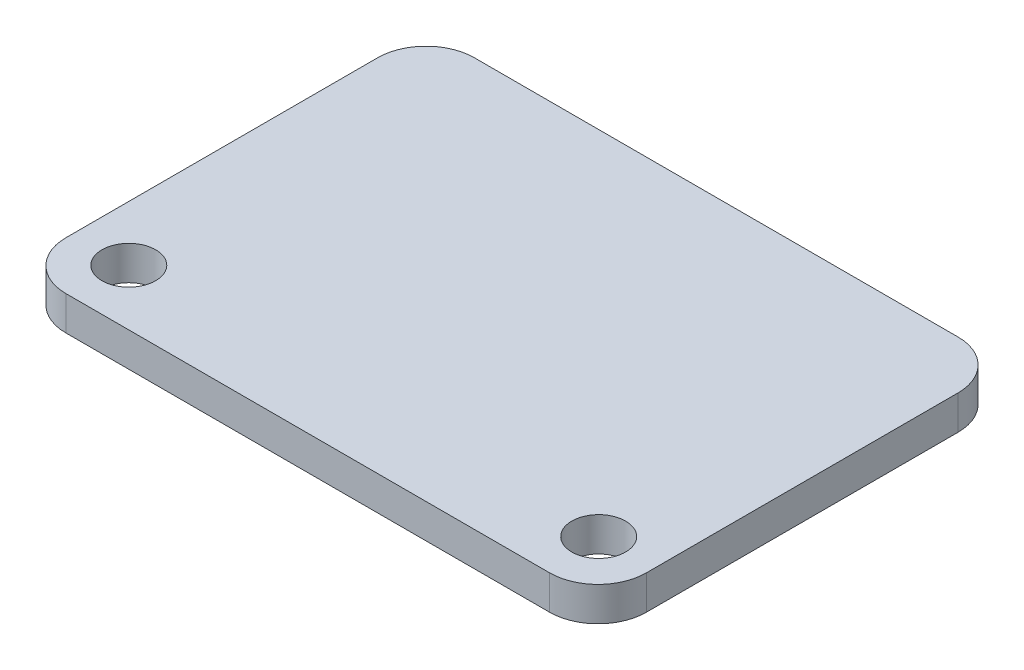
SolidWorks part; units mm, degrees
ref_plane "Front Plane" through (0, 0, 0) normal (0, 0, 1) x (1, 0, 0)
ref_plane "Top Plane" through (0, 0, 0) normal (0, 1, 0) x (1, 0, 0)
ref_plane "Right Plane" through (0, 0, 0) normal (1, 0, 0) x (0, 0, -1)
sketch "Sketch1" plane through (0, 0, 0) normal (0, 1, 0) x (1, 0, 0)
  line L1 (-13.5, -9.5) -> (13.5, -9.5)
  line L2 (-13.5, -9.5) -> (-13.5, 9.5)
  line L3 (-13.5, 9.5) -> (13.5, 9.5)
  line L4 (13.5, -9.5) -> (13.5, 9.5)
  line L5 (-13.5, -9.5) -> (13.5, 9.5) construction
  line L6 (-13.5, 9.5) -> (13.5, -9.5) construction
  point P0 (0, 0)
  dimension "D1" = 27
  dimension "D2" = 19
extrude "Boss-Extrude1" add sketch "Sketch1" along normal blind 1.5875
fillet "Fillet1" radius 2.25 4 edges at (-13.5, 0.7937, 9.5) (13.5, 0.7937, 9.5) (13.5, 0.7937, -9.5) (-13.5, 0.7937, -9.5)
sketch "Sketch3" plane through (0, 1.5875, 0) normal (0, 1, 0) x (1, 0, 0)
  line L0 (-9.679, -6.8961) -> (9.679, -6.8961) construction
  line L1 (0, -6.8961) -> (0, -4.0401) construction
  circle A0 centre (-10.929, -6.8961) radius 1.25
  circle A1 centre (10.929, -6.8961) radius 1.25
  dimension "D1" = 2.5
  dimension "D2" = 2.5
extrude "Cut-Extrude1" cut sketch "Sketch3" against normal through all
